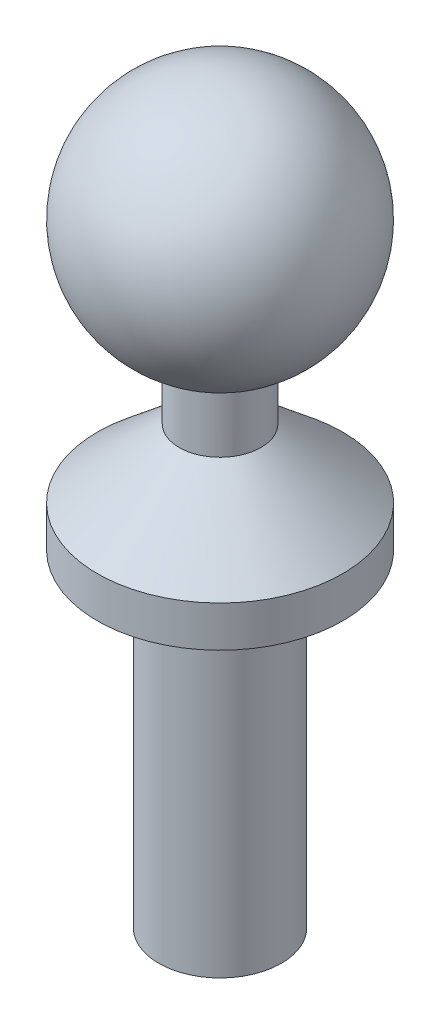
SolidWorks part; units mm, degrees
ref_plane "Plan de face" through (0, 0, 0) normal (0, 0, 1) x (1, 0, 0)
ref_plane "Plan de dessus" through (0, 0, 0) normal (0, 1, 0) x (1, 0, 0)
ref_plane "Plan de droite" through (0, 0, 0) normal (1, 0, 0) x (0, 0, -1)
sketch "Esquisse1" plane through (0, 0, 0) normal (0, 0, 1) x (1, 0, 0)
  line L0 (0, -15) -> (0, 0) construction
  line L1 (0, -15) -> (1.5, -15)
  line L2 (1.5, -15) -> (1.5, -7)
  line L3 (1.5, -7) -> (3, -7)
  line L4 (3, -7) -> (3, -6)
  line L5 (3, -6) -> (1, -4.3284)
  line L9 (1, -4.3284) -> (1, -2.8284)
  line L10 (0, -15) -> (0, 3)
  line L13 (0, 0) -> (0, 18.3443) construction
  arc A0 (1, -2.8284) -> (0, 3) centre (0, 0) ccw
  point P3 (0, 11.4358)
  dimension "D6" = 6
  dimension "D1" = 15
  dimension "D2" = 1.5
  dimension "D3" = 10
  dimension "D4" = 3
  dimension "D5" = 1
  dimension "D7" = 1
  dimension "D8" = 1.5
revolve "Révolution2" add sketch "Esquisse1" angle 360 about L10
sketch "Esquisse2" plane through (0, 0, 0) normal (0, 0, 1) x (1, 0, 0)
  point P0 (0, 0)
